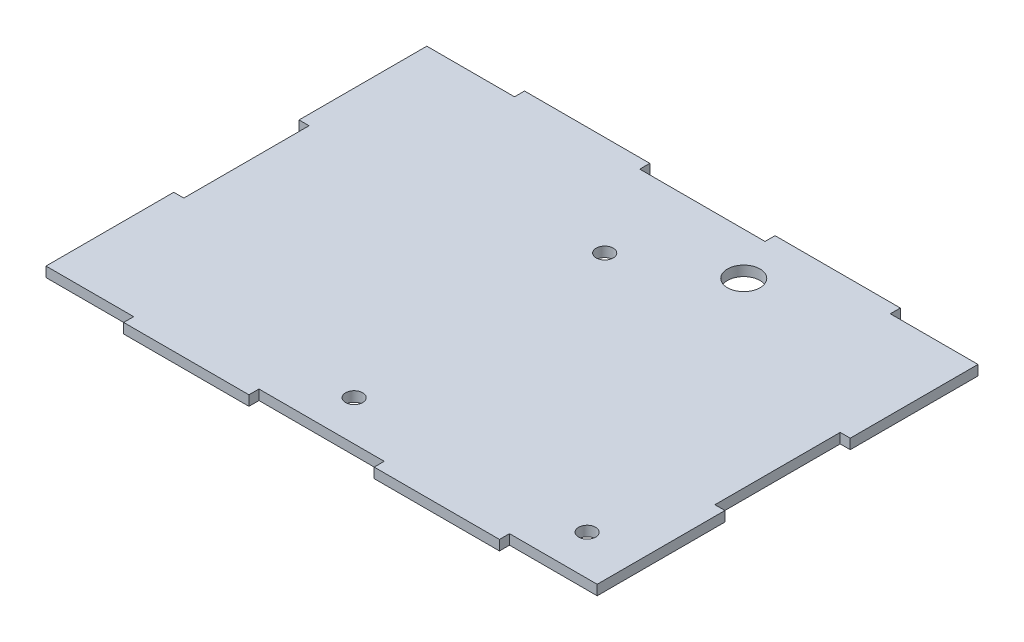
SolidWorks part; units mm, degrees
ref_plane "Front Plane" through (0, 0, 0) normal (0, 0, 1) x (1, 0, 0)
ref_plane "Top Plane" through (0, 0, 0) normal (0, 1, 0) x (1, 0, 0)
ref_plane "Right Plane" through (0, 0, 0) normal (1, 0, 0) x (0, 0, -1)
sketch "Sketch2" plane through (0, 0, 0) normal (0, 1, 0) x (1, 0, 0)
  line L0 (-110, 76) -> (-110, 25)
  line L1 (-75, -80) -> (-25, -80)
  line L2 (110, -76) -> (110, -25)
  line L3 (75, 80) -> (25, 80)
  line L4 (-110, -76) -> (-75, -76)
  line L5 (-25, -76) -> (-25, -80)
  line L6 (25, -76) -> (25, -80)
  line L7 (-75, -80) -> (-75, -76)
  line L8 (75, -80) -> (75, -76)
  line L9 (25, -80) -> (75, -80)
  line L10 (75, -76) -> (110, -76)
  line L11 (-25, -76) -> (25, -76)
  line L12 (-110, 76) -> (-75, 76)
  line L13 (-25, 80) -> (-25, 76)
  line L14 (25, 80) -> (25, 76)
  line L15 (-75, 76) -> (-75, 80)
  line L16 (75, 80) -> (75, 76)
  line L17 (-25, 76) -> (25, 76)
  line L18 (-25, 80) -> (-75, 80)
  line L19 (75, 76) -> (110, 76)
  line L20 (-106, 25) -> (-106, -25)
  line L21 (106, 25) -> (106, -25)
  line L22 (-106, 25) -> (-110, 25)
  line L23 (-106, -25) -> (-110, -25)
  line L24 (106, -25) -> (110, -25)
  line L25 (106, 25) -> (110, 25)
  line L26 (-110, -25) -> (-110, -76)
  line L27 (110, 25) -> (110, 76)
  dimension "D1" = 4
  dimension "D2" = 50
  dimension "D3" = 110
  dimension "D4" = 80
  dimension "D5" = 4
  dimension "D6" = 50
  dimension "D7" = 25
  dimension "D8" = 50
  dimension "D9" = 50
  dimension "D10" = 25
  dimension "D11" = 50
  dimension "D12" = 50
  dimension "D13" = 160
  dimension "D14" = 110
  dimension "D15" = 4
  dimension "D16" = 4
  dimension "D17" = 50
  dimension "D18" = 50
  dimension "D19" = 25
  dimension "D20" = 25
extrude "Boss-Extrude1" add sketch "Sketch2" along normal blind 4
sketch "Sketch3" plane through (0, 4, 0) normal (0, 1, 0) x (1, 0, 0)
  line L0 (25, -80) -> (75, -80) construction
  line L1 (110, -76) -> (110, -25) construction
  circle A0 centre (90, -60) radius 3.41
  circle A1 centre (-3, -60) radius 3.41
  circle A2 centre (-3, 40) radius 3.41
  point P6 (0, 0)
  point P7 (0, 0)
  point P12 (0, 0)
  dimension "D1" = 6.82
  dimension "D2" = 6.82
  dimension "D3" = 6.82
  dimension "D4" = 20
  dimension "D5" = 20
  dimension "D6" = 93
  dimension "D7" = 100
extrude "Cut-Extrude1" cut sketch "Sketch3" against normal through all
sketch "Sketch4" plane through (0, 4, 0) normal (0, 1, 0) x (1, 0, 0)
  line L0 (25, -80) -> (75, -80) construction
  line L1 (110, 25) -> (110, 76) construction
  circle A0 centre (33.5, 59) radius 6.5
  dimension "D2" = 13
  dimension "D1" = 139
  dimension "D3" = 76.5
extrude "Cut-Extrude2" cut sketch "Sketch4" against normal through all
